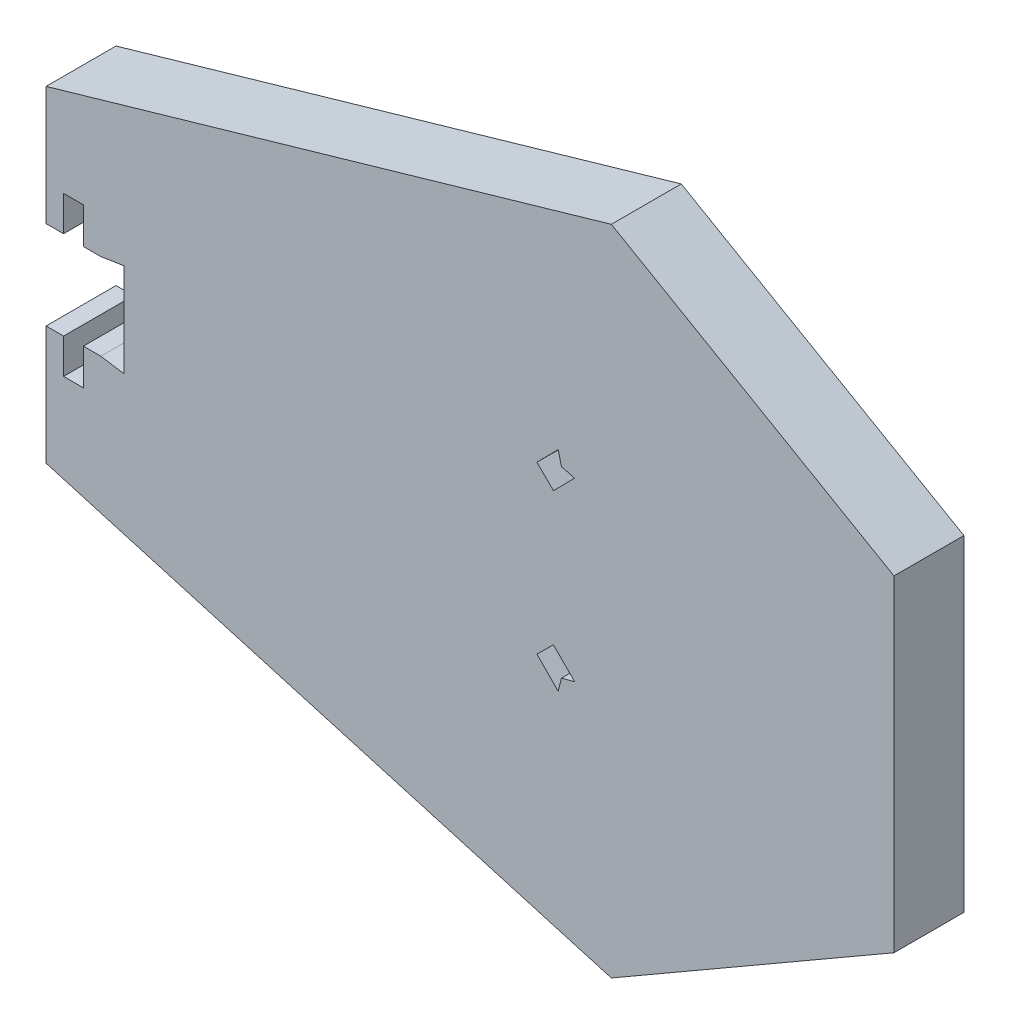
SolidWorks part; units mm, degrees
ref_plane "Front Plane" through (0, 0, 0) normal (0, 0, 1) x (1, 0, 0)
ref_plane "Top Plane" through (0, 0, 0) normal (0, 1, 0) x (1, 0, 0)
ref_plane "Right Plane" through (0, 0, 0) normal (1, 0, 0) x (0, 0, -1)
sketch "Sketch1" plane through (0, 0, 0) normal (0, 0, 1) x (1, 0, 0)
  line L0 (31.2231, 14) -> (6.9744, 28) construction
  line L1 (31.2231, -14) -> (31.2231, 14) construction
  line L2 (6.9744, -28) -> (31.2231, -14) construction
  line L3 (6.9744, -28) -> (-41.5231, -14) construction
  line L4 (-41.5231, 14) -> (-41.5231, -14) construction
  line L5 (-41.5231, 14) -> (6.9744, 28) construction
  line L6 (31.2231, 14) -> (6.9744, 28)
  line L7 (31.2231, -14) -> (31.2231, 14)
  line L8 (6.9744, -28) -> (31.2231, -14)
  line L9 (6.9744, -28) -> (-41.5231, -14)
  line L10 (-41.5231, 14) -> (-41.5231, -14)
  line L11 (-41.5231, 14) -> (6.9744, 28)
  line L18 (-41.5231, 3.7) -> (-36.8231, 3.7)
  line L19 (-36.8231, 3.7) -> (-34.8231, 4.0157)
  line L20 (-16.8732, 6.8495) -> (-36.8231, 3.7) construction
  line L21 (-34.8231, 4.0157) -> (-34.8231, -4.0157)
  line L23 (-16.8732, -6.8495) -> (-36.8231, -3.7) construction
  line L24 (-34.8231, -4.0157) -> (-36.8231, -3.7)
  line L25 (-36.8231, -3.7) -> (-41.5231, -3.7)
  line L26 (-39.9231, 3.7) -> (-38.3231, 3.7) construction
  line L27 (-36.8231, 3.7) -> (-36.8231, 1.4) construction
  line L28 (-41.5231, 0) -> (31.2231, 0) construction
  line L29 (2.4087, -8.9791) -> (0.5844, -7.1276)
  line L30 (0.5844, -7.1276) -> (2.009, -5.7239)
  line L31 (2.009, -5.7239) -> (3.8193, -7.5613)
  line L32 (3.8193, -7.5613) -> (2.7004, -7.8504)
  line L33 (2.7004, 7.8504) -> (2.4087, 8.9791)
  line L34 (2.7004, 7.8504) -> (2.4087, 8.9791)
  line L35 (3.8193, 7.5613) -> (2.7004, 7.8504)
  line L36 (3.8193, 7.5613) -> (2.7004, 7.8504)
  line L37 (2.009, 5.7239) -> (3.8193, 7.5613)
  line L38 (2.009, 5.7239) -> (3.8193, 7.5613)
  line L39 (0.5844, 7.1276) -> (2.009, 5.7239)
  line L40 (0.5844, 7.1276) -> (2.009, 5.7239)
  line L41 (2.4087, 8.9791) -> (0.5844, 7.1276)
  line L42 (2.4087, 8.9791) -> (0.5844, 7.1276)
  line L43 (2.7004, -7.8504) -> (2.4087, -8.9791)
  dimension "D1" = 2
  dimension "D2" = 0
extrude "Boss-Extrude1" add sketch "Sketch1" along normal blind 6
sketch "Sketch2" plane through (0, 0, 6) normal (0, 0, 1) x (1, 0, 0)
  line L20 (-41.6231, -3.4275) -> (-41.6231, -3.8)
  line L21 (-41.6231, -3.8) -> (-40.0231, -3.8)
  line L22 (-40.0231, -3.8) -> (-40.0231, -6.8)
  line L23 (-40.0231, -6.8) -> (-38.3231, -6.8)
  line L24 (-38.3231, -6.8) -> (-38.3231, 6.8)
  line L25 (-38.3231, 6.8) -> (-40.0231, 6.8)
  line L26 (-40.0231, 6.8) -> (-40.0231, 3.8)
  line L27 (-40.0231, 3.8) -> (-41.6231, 3.8)
  line L28 (-41.6231, 3.8) -> (-41.6231, 3.4275)
  line L29 (-41.6231, 3.4275) -> (-41.6231, -3.4275)
  line L30 (-41.6231, -3.4275) -> (-41.6231, -3.8)
  line L31 (-41.6231, -3.8) -> (-40.0231, -3.8)
  line L32 (-40.0231, -3.8) -> (-40.0231, -6.8)
  line L33 (-40.0231, -6.8) -> (-38.3231, -6.8)
  line L34 (-38.3231, -6.8) -> (-38.3231, 6.8)
  line L35 (-38.3231, 6.8) -> (-40.0231, 6.8)
  line L36 (-40.0231, 6.8) -> (-40.0231, 3.8)
  line L37 (-40.0231, 3.8) -> (-41.6231, 3.8)
  line L38 (-41.6231, 3.8) -> (-41.6231, 3.4275)
  line L39 (-41.6231, 3.4275) -> (-41.6231, -3.4275)
  dimension "D1" = 0.1
extrude "Cut-Extrude1" cut sketch "Sketch2" against normal through all
sketch "Sketch3" plane through (0, 0, 6) normal (0, 0, 1) x (1, 0, 0)
  line L0 (6.9744, 28) -> (6.9744, -28) construction
  line L1 (31.2231, 0) -> (6.9744, 0) construction
  line L2 (31.2231, -14) -> (31.2231, 14) construction
ref_plane "Plane1" through (0, 0, 0) normal (0, 1, 0) x (-1, 0, 0)
